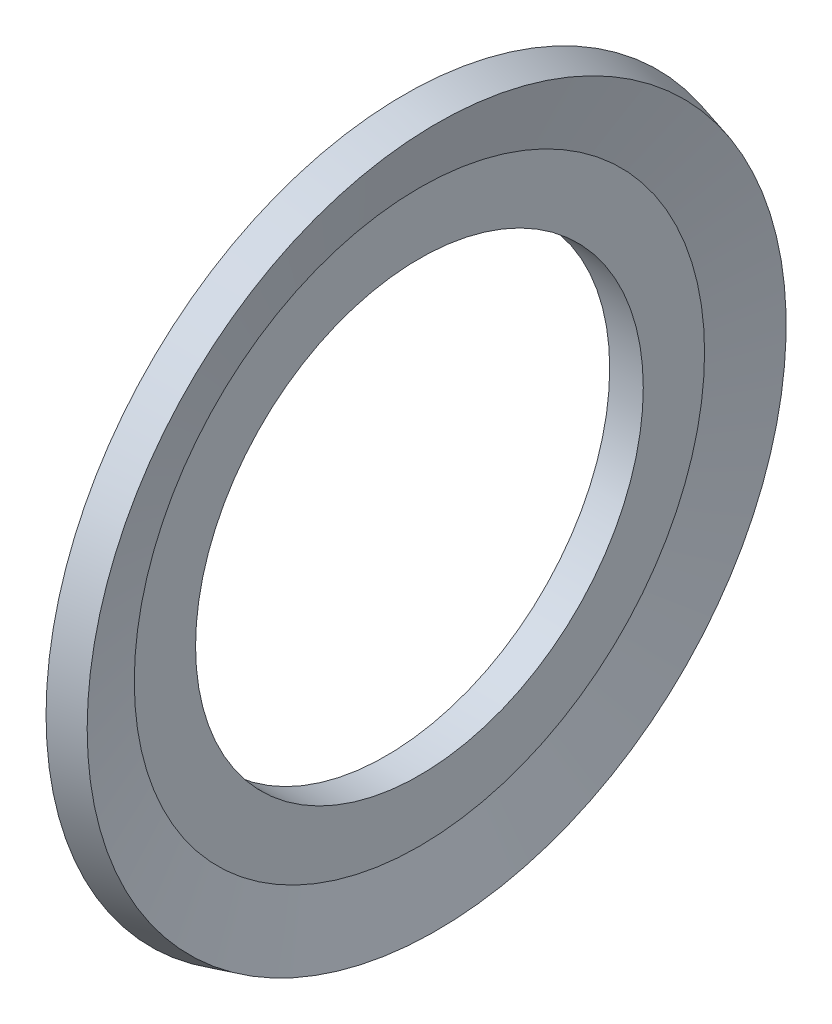
SolidWorks part; units mm, degrees
ref_plane "Front Plane" through (0, 0, 0) normal (0, 0, 1) x (1, 0, 0)
ref_plane "Top Plane" through (0, 0, 0) normal (0, 1, 0) x (1, 0, 0)
ref_plane "Right Plane" through (0, 0, 0) normal (1, 0, 0) x (0, 0, -1)
sketch "Sketch1" plane through (0, 0, 0) normal (0, 0, 1) x (1, 0, 0)
  line L0 (0, 0) -> (2.2702, 0) construction
  line L1 (0, 10) -> (0, 12.935)
  line L2 (0, 12.935) -> (0.8213, 16)
  line L3 (0.8213, 16) -> (2.2702, 15.6118)
  line L4 (2.2702, 15.6118) -> (1.5, 12.7375)
  line L5 (1.5, 12.7375) -> (1.5, 10)
  line L6 (1.5, 10) -> (0, 10)
  dimension "D1" = 15
  dimension "MSM_1" = 1.5
  dimension "E" = 20
  dimension "F_1" = 32
  dimension "P.D." = 25.87
revolve "Revolve1" add sketch "Sketch1" angle 360 about L0
sketch "Sketch2" [suppressed] plane through (0, 0, 0) normal (0, 0, 1) x (1, 0, 0)
  line L0 (2.4631, 23.6118) -> (2.4631, -23.6118) construction
  line L1 (0, 24) -> (2.4631, 24)
  line L2 (0, 24) -> (0, 23)
  line L3 (0, 23) -> (2.4631, 23)
  line L4 (2.4631, 24) -> (2.4631, 23)
  line L5 (0, 20.215) -> (0, -20.215) construction
  line L6 (0, 0) -> (2.4631, 0) construction
  dimension "FC" = 46
revolve "Cut-Revolve1" [suppressed] cut sketch "Sketch2" angle 360 about L6
